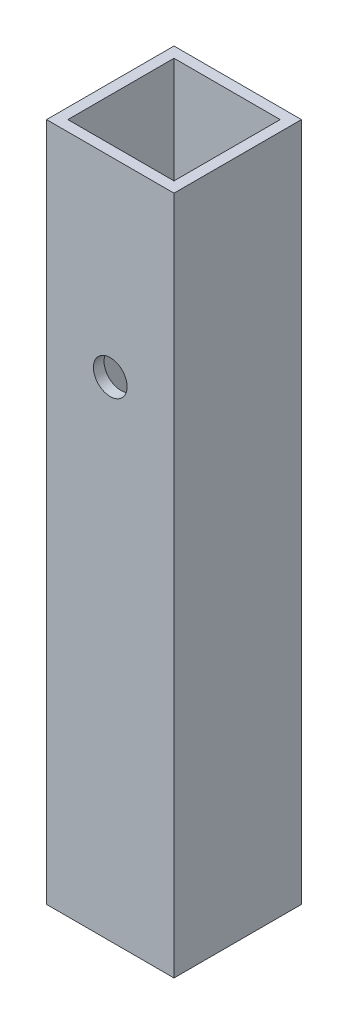
SolidWorks part; units mm, degrees
material "Plain Carbon Steel"
ref_plane "Front Plane" through (0, 0, 0) normal (0, 0, 1) x (1, 0, 0)
ref_plane "Top Plane" through (0, 0, 0) normal (0, 1, 0) x (1, 0, 0)
ref_plane "Right Plane" through (0, 0, 0) normal (1, 0, 0) x (0, 0, -1)
sketch "Sketch1" plane through (0, 0, 0) normal (0, 1, 0) x (1, 0, 0)
  line L0 (0, 19.05) -> (3.175, 19.05) construction
  line L1 (0, 0) -> (38.1, 0)
  line L2 (0, 0) -> (0, 38.1)
  line L3 (0, 38.1) -> (38.1, 38.1)
  line L4 (38.1, 0) -> (38.1, 38.1)
  line L5 (3.175, 3.175) -> (34.925, 3.175)
  line L6 (3.175, 3.175) -> (3.175, 34.925)
  line L7 (3.175, 34.925) -> (34.925, 34.925)
  line L8 (34.925, 3.175) -> (34.925, 34.925)
  line L9 (34.925, 19.05) -> (38.1, 19.05) construction
  line L10 (19.05, 3.175) -> (19.05, 0) construction
  line L11 (19.05, 34.925) -> (19.05, 38.1) construction
  dimension "D1" = 38.1
  dimension "D2" = 38.1
  dimension "D3" = 3.175
extrude "Boss-Extrude1" add sketch "Sketch1" along normal blind 203.2
hole_wizard "X (0.397) Diameter Hole1" positions "Sketch3" profile "Sketch2" hole size "X" standard "ANSI Inch" end condition through all
sketch "Sketch3" plane through (0, 0, 0) normal (0, 0, 1) x (1, 0, 0)
  line L0 (19.05, 0) -> (19.05, 146.05) construction
  line L1 (0, 0) -> (38.1, 0) construction
  line L2 (19.05, 146.05) -> (19.05, 203.2) construction
  line L3 (0, 203.2) -> (38.1, 203.2) construction
  point P0 (19.05, 146.05)
  dimension "D1" = 146.05
sketch "Sketch2" plane through (19.05, 146.05, 0) normal (1, 0, 0) x (0, -1, 0)
  line L0 (0, 0) -> (0, 38.1)
  line L1 (0, 38.1) -> (5.0419, 38.1)
  line L2 (5.0419, 38.1) -> (5.0419, 0)
  line L5 (5.0419, 0) -> (0, 0)
  line L11 (0, -6.35) -> (0, 107.95) construction
  dimension "Thru Hole Dia." = 10.0838
  dimension "Thru Hole Depth" = 38.1
